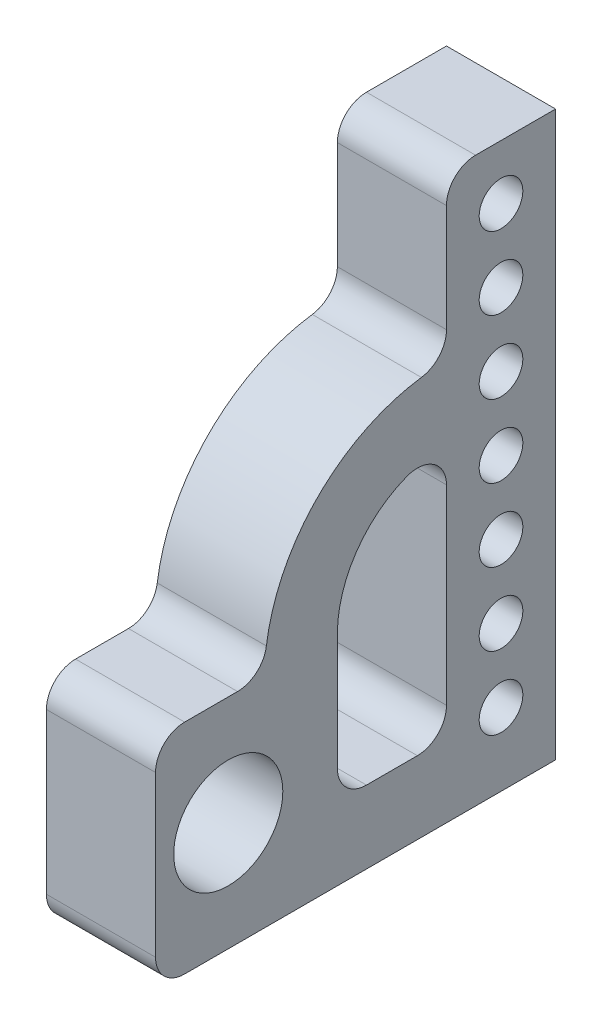
SolidWorks part; units mm, degrees
ref_plane "Front Plane" through (0, 0, 0) normal (1, 0, 0) x (0, 1, 0)
ref_plane "Top Plane" through (0, 0, 0) normal (0, 0, 1) x (0, 1, 0)
ref_plane "Right Plane" through (0, 0, 0) normal (0, 1, 0) x (-1, 0, 0)
sketch "Sketch1" plane through (0, 0, 0) normal (1, 0, 0) x (0, 1, 0)
  line L0 (0, 0) -> (0, 110)
  line L1 (0, 110) -> (60, 110)
  line L2 (60, 110) -> (60, 80)
  line L3 (0, 0) -> (155, 0)
  line L4 (155, 0) -> (155, 30)
  line L5 (155, 30) -> (110, 30)
  line L6 (90, 30) -> (20, 30)
  line L7 (20, 30) -> (20, 60)
  line L8 (20, 60) -> (60, 60)
  line L9 (60, 80) -> (60, 15) construction
  line L10 (20, 15) -> (20, 30) construction
  arc A0 (60, 80) -> (110, 30) centre (60, 30) cw
  arc A1 (60, 60) -> (90, 30) centre (60, 30) cw
  circle A2 centre (30, 90) radius 15
  circle A9 centre (20, 15) radius 6
  circle A10 centre (40, 15) radius 6
  circle A11 centre (60, 15) radius 6
  circle A12 centre (80, 15) radius 6
  circle A13 centre (100, 15) radius 6
  circle A14 centre (120, 15) radius 6
  circle A15 centre (140, 15) radius 6
  point P17 (60.4879, 15)
  dimension "D6" = 50
  dimension "D7" = 20
  dimension "D11" = 30
  dimension "D16" = 12
  dimension "D1" = 60
  dimension "D2" = 110
  dimension "D3" = 155
  dimension "D4" = 30
  dimension "D5" = 30
  dimension "D8" = 30
  dimension "D9" = 30
  dimension "D10" = 7
  dimension "D12" = 20
  dimension "D13" = 30
  dimension "D14" = 15
  dimension "D15" = 120
extrude "Boss-Extrude1" add sketch "Sketch1" along normal blind 30 contours A2 | A0 L2 L1 L0 L3 L4 L5 A15 A14 A13 A12 A11 A10 A9 A2 L8 A1 L6 L7
fillet "Fillet1" radius 8 8 edges at (15, 90, 30) (15, 20, 60) (15, 20, 30) (15, 155, 30) (15, 110, 30) (15, 60, 80) (15, 0, 110) (15, 60, 110)
